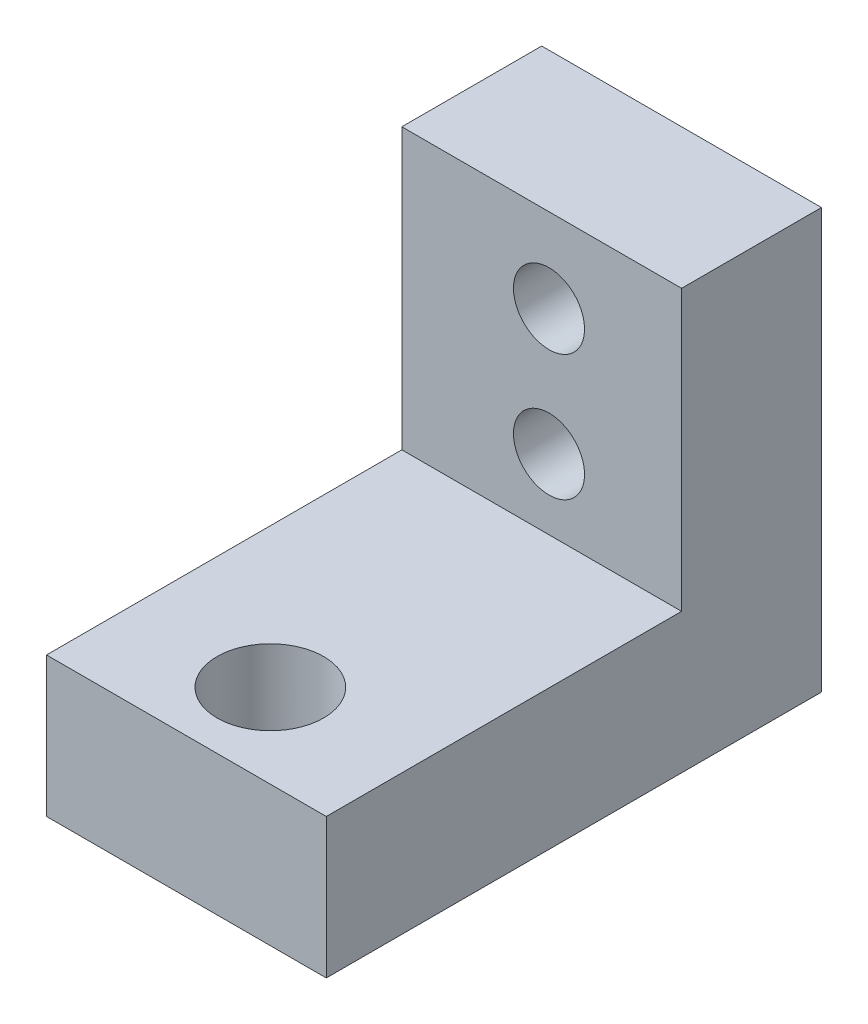
SolidWorks part; units mm, degrees
material "Delrin 2700 NC010, Low Viscosity Acetal Copolymer (SS)"
ref_plane "Front Plane" through (0, 0, 0) normal (0, 0, 1) x (1, 0, 0)
ref_plane "Top Plane" through (0, 0, 0) normal (0, 1, 0) x (1, 0, 0)
ref_plane "Right Plane" through (0, 0, 0) normal (1, 0, 0) x (0, 0, -1)
sketch "Sketch1" plane through (0, 0, 0) normal (0, 1, 0) x (1, 0, 0)
  line L1 (0, 0) -> (20, 0)
  line L2 (0, 0) -> (0, 25.4)
  line L3 (0, 25.4) -> (20, 25.4)
  line L4 (20, 0) -> (20, 25.4)
  dimension "D1" = 25.4
  dimension "D2" = 20
extrude "Boss-Extrude1" add sketch "Sketch1" along normal blind 10
sketch "Sketch2" plane through (0, 0, 0) normal (0, 1, 0) x (1, 0, 0)
  line L0 (20, 0) -> (20, 25.4) construction
  line L1 (0, 25.4) -> (20, 25.4)
  line L2 (0, 25.4) -> (0, 35.4)
  line L3 (0, 35.4) -> (20, 35.4)
  line L4 (20, 25.4) -> (20, 35.4)
  dimension "D1" = 10
extrude "Boss-Extrude2" add sketch "Sketch2" along normal blind 30
sketch "Sketch3" plane through (0, 10, 0) normal (0, 1, 0) x (1, 0, 0)
  line L0 (0, 0) -> (20, 0) construction
  circle A0 centre (10, 6) radius 3.81
  point P5 (10, 0)
  dimension "D1" = 7.62
  dimension "D2" = 6
extrude "Cut-Extrude1" cut sketch "Sketch3" against normal blind 30
sketch "Sketch4" plane through (0, 0, -35.4) normal (0, 0, -1) x (-1, 0, 0)
  line L0 (-20, 30) -> (0, 30) construction
  line L1 (-20, 10) -> (0, 10) construction
  circle A0 centre (-10.522, 24) radius 2.54
  circle A1 centre (-10.522, 15) radius 2.54
  dimension "D1" = 5.08
  dimension "D2" = 6
  dimension "D3" = 5
extrude "Cut-Extrude2" cut sketch "Sketch4" against normal blind 30
